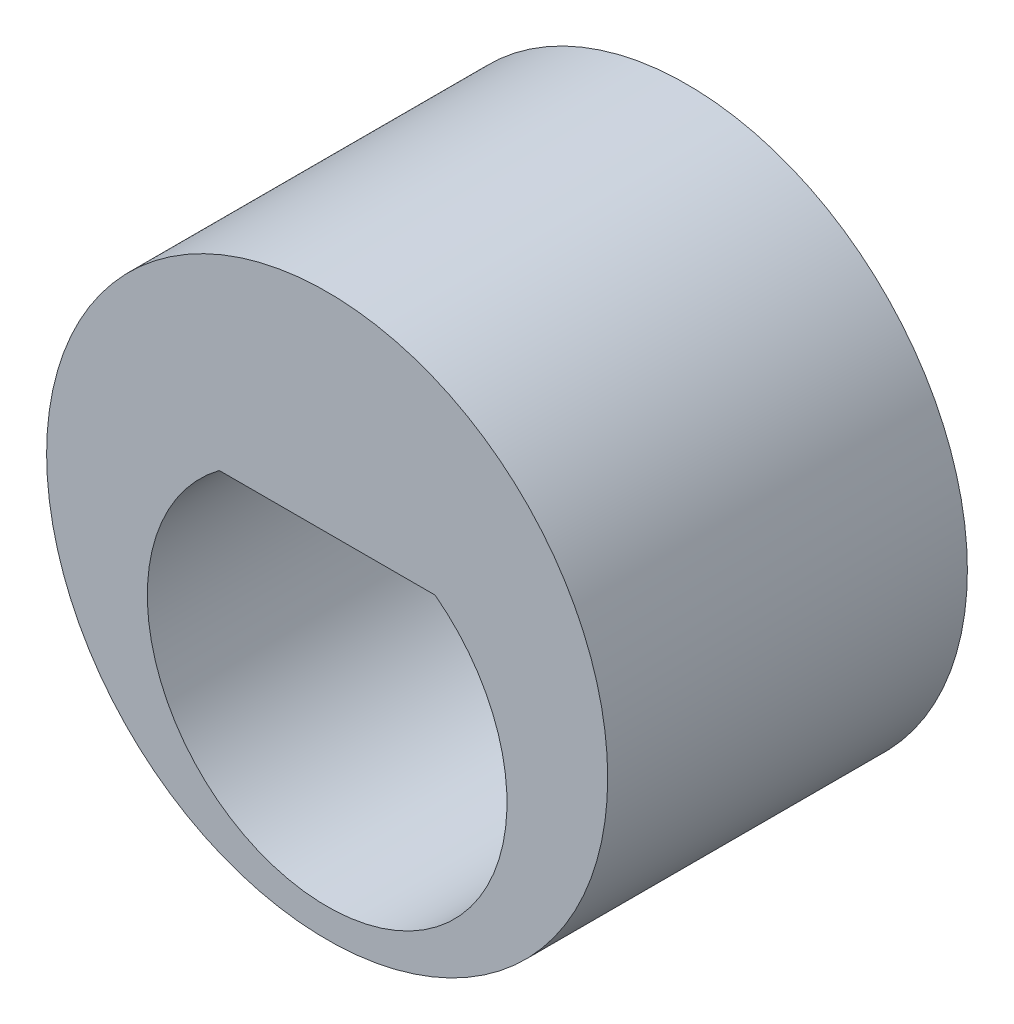
SolidWorks part; units mm, degrees
ref_plane "Plan de face" through (0, 0, 0) normal (0, 0, 1) x (1, 0, 0)
ref_plane "Plan de dessus" through (0, 0, 0) normal (0, 1, 0) x (1, 0, 0)
ref_plane "Plan de droite" through (0, 0, 0) normal (1, 0, 0) x (0, 0, -1)
sketch "Esquisse1" plane through (0, 0, 0) normal (0, 0, 1) x (1, 0, 0)
  line L0 (-1.5, 2) -> (1.5, 2)
  arc A0 (-1.5, 2) -> (1.5, 2) centre (0, 0) ccw
  circle A2 centre (0, 1) radius 3.9
  dimension "D1" = 2.5
  dimension "D2" = 2
  dimension "D4" = 7.8
  dimension "D5" = 1
extrude "Boss.-Extru.1" add sketch "Esquisse1" along normal blind 5
